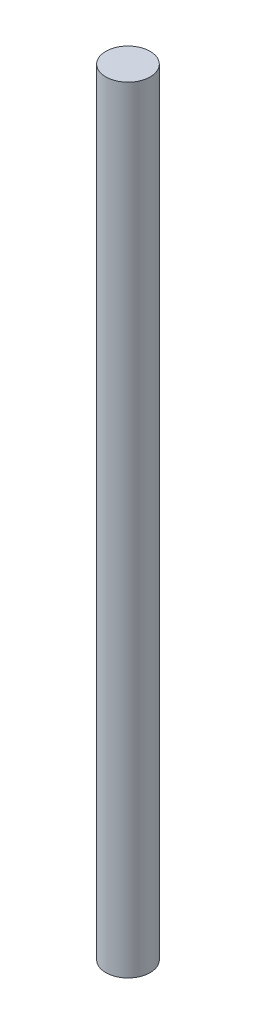
SolidWorks part; units mm, degrees
ref_plane "Front Plane" through (0, 0, 0) normal (0, 0, 1) x (1, 0, 0)
ref_plane "Top Plane" through (0, 0, 0) normal (0, 1, 0) x (1, 0, 0)
ref_plane "Right Plane" through (0, 0, 0) normal (1, 0, 0) x (0, 0, -1)
sketch "Sketch2" plane through (0, 0, 0) normal (0, 1, 0) x (1, 0, 0)
  circle A0 centre (0, 0) radius 4
  dimension "D1" = 8
extrude "Boss-Extrude2" add sketch "Sketch2" along normal blind 140
